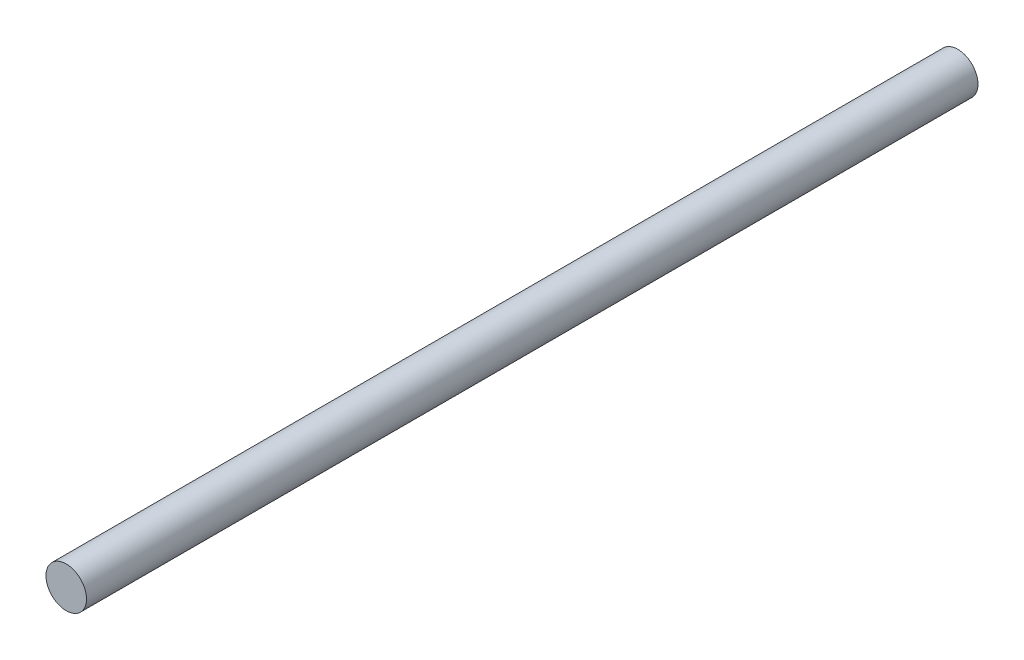
SolidWorks part; units mm, degrees
ref_plane "Front Plane" through (0, 0, 0) normal (0, 0, 1) x (1, 0, 0)
ref_plane "Top Plane" through (0, 0, 0) normal (0, 1, 0) x (1, 0, 0)
ref_plane "Right Plane" through (0, 0, 0) normal (1, 0, 0) x (0, 0, -1)
sketch "Sketch1" plane through (0, 0, 0) normal (0, 0, 1) x (1, 0, 0)
  circle A0 centre (0, 0) radius 6.35
  dimension "D1" = 12.7
extrude "Boss-Extrude1" add sketch "Sketch1" along normal blind 279.4
